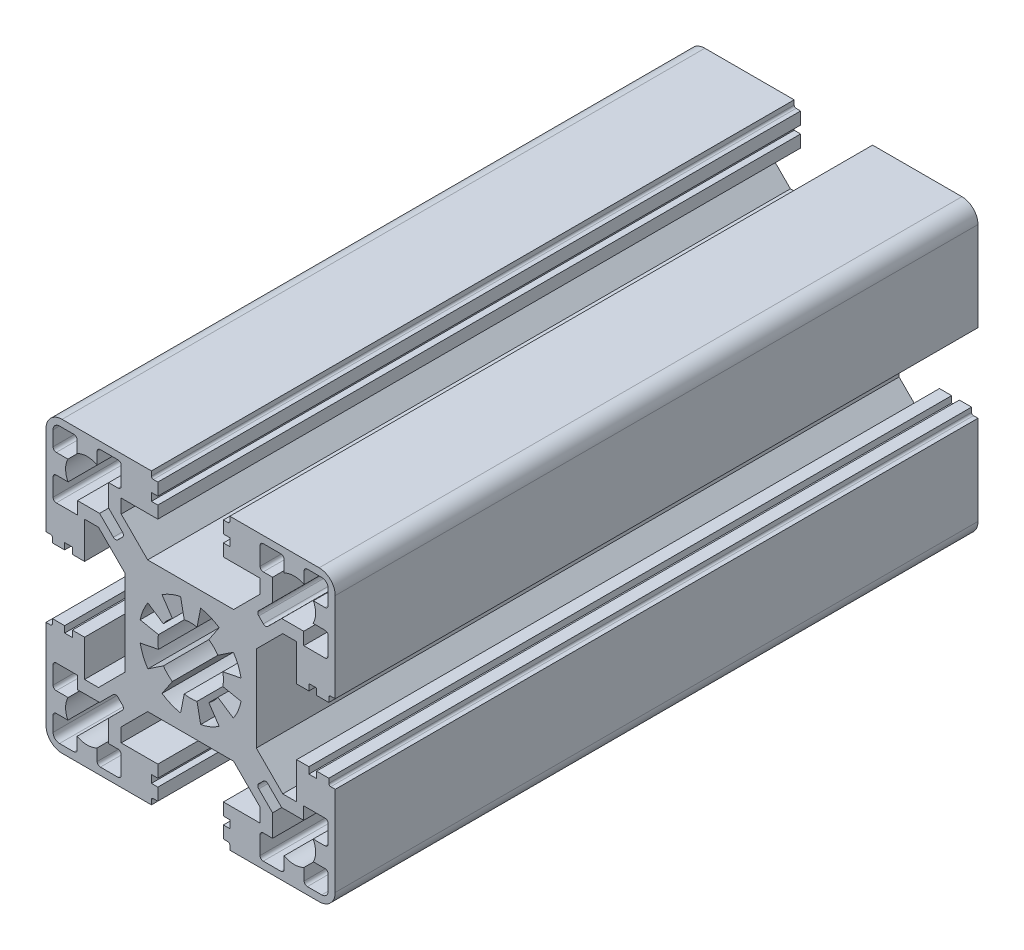
SolidWorks part; units mm, degrees
ref_plane "前视基准面" through (0, 0, 0) normal (0, 0, 1) x (1, 0, 0)
ref_plane "上视基准面" through (0, 0, 0) normal (0, 1, 0) x (1, 0, 0)
ref_plane "右视基准面" through (0, 0, 0) normal (1, 0, 0) x (0, 0, -1)
sketch "草图1" plane through (0, 0, 0) normal (0, 0, 1) x (1, 0, 0)
  line L0 (-5.3716, 23.257) -> (-19.2716, 23.257)
  line L1 (-21.7716, 20.757) -> (-21.7716, 6.857)
  line L2 (-4.3716, 17.257) -> (-10.0716, 17.257)
  line L3 (-15.7716, 11.557) -> (-15.7716, 5.857)
  line L4 (-4.3716, 22.257) -> (-5.0716, 22.257)
  line L5 (-5.3716, 22.557) -> (-5.3716, 23.257)
  line L6 (-21.7716, 6.857) -> (-21.0716, 6.857)
  line L7 (-20.7716, 6.557) -> (-20.7716, 5.857)
  line L8 (-15.7716, 11.557) -> (-13.6071, 11.557)
  line L9 (-18.8716, 6.857) -> (-17.6716, 6.857)
  line L10 (-20.7716, 5.857) -> (-18.8716, 5.857)
  line L11 (-17.6716, 5.857) -> (-15.7716, 5.857)
  line L12 (-10.0716, 17.257) -> (-10.0716, 15.0925)
  line L13 (-5.3716, 20.357) -> (-5.3716, 19.157)
  line L14 (-4.3716, 22.257) -> (-4.3716, 20.357)
  line L15 (-4.3716, 19.157) -> (-4.3716, 17.257)
  line L16 (-4.3716, 19.157) -> (-5.3716, 19.157)
  line L17 (-4.3716, 20.357) -> (-5.3716, 20.357)
  line L19 (-17.6716, 5.857) -> (-17.6716, 6.857)
  line L20 (-18.8716, 5.857) -> (-18.8716, 6.857)
  line L21 (6.8284, 23.257) -> (20.7284, 23.257)
  line L22 (23.2284, 20.757) -> (23.2284, 6.857)
  line L23 (5.8284, 17.257) -> (11.5284, 17.257)
  line L24 (17.2284, 11.557) -> (17.2284, 5.857)
  line L25 (5.8284, 22.257) -> (6.5284, 22.257)
  line L26 (6.8284, 22.557) -> (6.8284, 23.257)
  line L27 (23.2284, 6.857) -> (22.5284, 6.857)
  line L28 (22.2284, 6.557) -> (22.2284, 5.857)
  line L29 (17.2284, 11.557) -> (15.0639, 11.557)
  line L30 (20.3284, 6.857) -> (19.1284, 6.857)
  line L31 (22.2284, 5.857) -> (20.3284, 5.857)
  line L32 (19.1284, 5.857) -> (17.2284, 5.857)
  line L33 (11.5284, 17.257) -> (11.5284, 15.0925)
  line L34 (6.8284, 20.357) -> (6.8284, 19.157)
  line L35 (5.8284, 19.157) -> (6.8284, 19.157)
  line L36 (5.8284, 20.357) -> (6.8284, 20.357)
  line L38 (19.1284, 5.857) -> (19.1284, 6.857)
  line L39 (20.3284, 5.857) -> (20.3284, 6.857)
  line L40 (5.8284, 22.257) -> (5.8284, 20.357)
  line L41 (5.8284, 19.157) -> (5.8284, 17.257)
  line L42 (-5.3716, -21.743) -> (-19.2716, -21.743)
  line L43 (-21.7716, -19.243) -> (-21.7716, -5.343)
  line L44 (-4.3716, -15.743) -> (-10.0716, -15.743)
  line L45 (-15.7716, -10.043) -> (-15.7716, -4.343)
  line L46 (-4.3716, -20.743) -> (-5.0716, -20.743)
  line L47 (-5.3716, -21.043) -> (-5.3716, -21.743)
  line L48 (-21.7716, -5.343) -> (-21.0716, -5.343)
  line L49 (-20.7716, -5.043) -> (-20.7716, -4.343)
  line L50 (-15.7716, -10.043) -> (-13.6071, -10.043)
  line L51 (-18.8716, -5.343) -> (-17.6716, -5.343)
  line L52 (-20.7716, -4.343) -> (-18.8716, -4.343)
  line L53 (-17.6716, -4.343) -> (-15.7716, -4.343)
  line L54 (-10.0716, -15.743) -> (-10.0716, -13.5785)
  line L55 (-5.3716, -18.843) -> (-5.3716, -17.643)
  line L56 (-4.3716, -20.743) -> (-4.3716, -18.843)
  line L57 (-4.3716, -17.643) -> (-4.3716, -15.743)
  line L58 (-4.3716, -17.643) -> (-5.3716, -17.643)
  line L59 (-4.3716, -18.843) -> (-5.3716, -18.843)
  line L61 (-17.6716, -4.343) -> (-17.6716, -5.343)
  line L62 (-18.8716, -4.343) -> (-18.8716, -5.343)
  line L63 (6.8284, -21.743) -> (20.7284, -21.743)
  line L64 (23.2284, -19.243) -> (23.2284, -5.343)
  line L65 (5.8284, -15.743) -> (11.5284, -15.743)
  line L66 (17.2284, -10.043) -> (17.2284, -4.343)
  line L67 (5.8284, -20.743) -> (6.5284, -20.743)
  line L68 (6.8284, -21.043) -> (6.8284, -21.743)
  line L69 (23.2284, -5.343) -> (22.5284, -5.343)
  line L70 (22.2284, -5.043) -> (22.2284, -4.343)
  line L71 (17.2284, -10.043) -> (15.0639, -10.043)
  line L72 (20.3284, -5.343) -> (19.1284, -5.343)
  line L73 (22.2284, -4.343) -> (20.3284, -4.343)
  line L74 (19.1284, -4.343) -> (17.2284, -4.343)
  line L75 (11.5284, -15.743) -> (11.5284, -13.5785)
  line L76 (6.8284, -18.843) -> (6.8284, -17.643)
  line L77 (5.8284, -17.643) -> (6.8284, -17.643)
  line L78 (5.8284, -18.843) -> (6.8284, -18.843)
  line L80 (19.1284, -4.343) -> (19.1284, -5.343)
  line L81 (20.3284, -4.343) -> (20.3284, -5.343)
  line L82 (5.8284, -20.743) -> (5.8284, -18.843)
  line L83 (5.8284, -17.643) -> (5.8284, -15.743)
  line L84 (-9.4916, 7.4415) -> (-9.4916, -5.9275)
  line L85 (-5.9561, -9.463) -> (7.4129, -9.463)
  line L86 (10.9484, -5.9275) -> (10.9484, 7.4415)
  line L87 (7.4129, 10.977) -> (-5.9561, 10.977)
  line L88 (-3.7161, -5.8947) -> (-2.105, -3.4835)
  line L89 (-0.8323, -7.0893) -> (-0.2665, -4.245)
  line L90 (2.2891, -7.0893) -> (1.7234, -4.245)
  line L91 (5.173, -5.8947) -> (3.5618, -3.4835)
  line L92 (7.3802, -3.6875) -> (4.9689, -2.0764)
  line L93 (8.5747, -0.8037) -> (5.7304, -0.2379)
  line L94 (8.5747, 2.3177) -> (5.7304, 1.752)
  line L95 (7.3802, 5.2016) -> (4.9689, 3.5904)
  line L96 (5.173, 7.4088) -> (3.5618, 4.9975)
  line L97 (2.2891, 8.6033) -> (1.7234, 5.759)
  line L98 (-0.8323, 8.6033) -> (-0.2665, 5.759)
  line L99 (-3.7161, 7.4088) -> (-2.105, 4.9975)
  line L100 (-5.9233, 5.2016) -> (-3.5121, 3.5904)
  line L101 (-7.1179, 2.3177) -> (-4.2736, 1.752)
  line L102 (-7.1179, -0.8037) -> (-4.2736, -0.2379)
  line L103 (-5.9233, -3.6875) -> (-3.5121, -2.0764)
  line L104 (-10.0716, 15.0925) -> (-5.9561, 10.977)
  line L105 (-13.6071, 11.557) -> (-9.4916, 7.4415)
  line L106 (11.5284, 15.0925) -> (7.4129, 10.977)
  line L107 (15.0639, 11.557) -> (10.9484, 7.4415)
  line L108 (-10.0716, -13.5785) -> (-5.9561, -9.463)
  line L109 (-13.6071, -10.043) -> (-9.4916, -5.9275)
  line L110 (11.5284, -13.5785) -> (7.4129, -9.463)
  line L111 (15.0639, -10.043) -> (10.9484, -5.9275)
  line L113 (-20.6716, 21.157) -> (-20.6716, 18.857)
  line L114 (-20.1716, 18.357) -> (-18.367, 18.357)
  line L115 (-12.0216, 18.357) -> (-10.5716, 18.357)
  line L116 (-10.0716, 18.857) -> (-10.0716, 21.657)
  line L117 (-10.5716, 22.157) -> (-13.3116, 22.157)
  line L118 (-13.8116, 21.657) -> (-13.8116, 19.8216)
  line L120 (-16.9316, 19.8216) -> (-16.9316, 21.657)
  line L121 (-17.4316, 22.157) -> (-19.6716, 22.157)
  line L122 (-12.0216, 14.9212) -> (-12.0216, 18.357)
  line L123 (-13.4358, 13.507) -> (-11.2924, 11.3636)
  line L124 (-12.0216, 14.9212) -> (-9.8782, 12.7778)
  line L125 (-10.5853, 11.3636) -> (-9.8782, 12.0707)
  line L126 (-13.4358, 13.507) -> (-16.8716, 13.507)
  line L127 (-18.3362, 15.297) -> (-20.1716, 15.297)
  line L129 (-20.6716, 14.797) -> (-20.6716, 12.057)
  line L130 (-20.1716, 11.557) -> (-16.8716, 11.557)
  line L131 (-16.8716, 13.507) -> (-16.8716, 11.557)
  line L149 (13.4784, 18.357) -> (12.0284, 18.357)
  line L150 (11.5284, 18.857) -> (11.5284, 21.657)
  line L151 (12.0284, 22.157) -> (14.7684, 22.157)
  line L152 (15.2684, 21.657) -> (15.2684, 19.8216)
  line L153 (18.3884, 19.8216) -> (18.3884, 21.657)
  line L154 (18.8884, 22.157) -> (21.1284, 22.157)
  line L155 (22.1284, 21.157) -> (22.1284, 18.857)
  line L156 (21.6284, 18.357) -> (19.8238, 18.357)
  line L157 (19.793, 15.297) -> (21.6284, 15.297)
  line L158 (22.1284, 14.797) -> (22.1284, 12.057)
  line L159 (21.6284, 11.557) -> (18.3284, 11.557)
  line L160 (18.3284, 11.557) -> (18.3284, 13.507)
  line L161 (18.3284, 13.507) -> (14.8926, 13.507)
  line L162 (14.8926, 13.507) -> (12.7492, 11.3636)
  line L163 (12.0421, 11.3636) -> (11.335, 12.0707)
  line L164 (11.335, 12.7778) -> (13.4784, 14.9212)
  line L165 (13.4784, 14.9212) -> (13.4784, 18.357)
  line L166 (-12.0216, -16.818) -> (-10.5716, -16.818)
  line L167 (-10.0716, -17.318) -> (-10.0716, -20.118)
  line L168 (-10.5716, -20.618) -> (-13.3116, -20.618)
  line L169 (-13.8116, -20.118) -> (-13.8116, -18.2826)
  line L170 (-16.9316, -18.2826) -> (-16.9316, -20.118)
  line L171 (-17.4316, -20.618) -> (-19.6716, -20.618)
  line L172 (-20.6716, -19.618) -> (-20.6716, -17.318)
  line L173 (-20.1716, -16.818) -> (-18.367, -16.818)
  line L174 (-18.3362, -13.758) -> (-20.1716, -13.758)
  line L175 (-20.6716, -13.258) -> (-20.6716, -10.518)
  line L176 (-20.1716, -10.018) -> (-16.8716, -10.018)
  line L177 (-16.8716, -10.018) -> (-16.8716, -11.968)
  line L178 (-16.8716, -11.968) -> (-13.4358, -11.968)
  line L179 (-13.4358, -11.968) -> (-11.2924, -9.8246)
  line L180 (-10.5853, -9.8246) -> (-9.8782, -10.5317)
  line L181 (-9.8782, -11.2388) -> (-12.0216, -13.3822)
  line L182 (-12.0216, -13.3822) -> (-12.0216, -16.818)
  line L183 (13.4784, -16.818) -> (12.0284, -16.818)
  line L184 (11.5284, -17.318) -> (11.5284, -20.118)
  line L185 (12.0284, -20.618) -> (14.7684, -20.618)
  line L186 (15.2684, -20.118) -> (15.2684, -18.2826)
  line L187 (18.3884, -18.2826) -> (18.3884, -20.118)
  line L188 (18.8884, -20.618) -> (21.1284, -20.618)
  line L189 (22.1284, -19.618) -> (22.1284, -17.318)
  line L190 (21.6284, -16.818) -> (19.8238, -16.818)
  line L191 (19.793, -13.758) -> (21.6284, -13.758)
  line L192 (22.1284, -13.258) -> (22.1284, -10.518)
  line L193 (21.6284, -10.018) -> (18.3284, -10.018)
  line L194 (18.3284, -10.018) -> (18.3284, -11.968)
  line L195 (18.3284, -11.968) -> (14.8926, -11.968)
  line L196 (14.8926, -11.968) -> (12.7492, -9.8246)
  line L197 (12.0421, -9.8246) -> (11.335, -10.5317)
  line L198 (11.335, -11.2388) -> (13.4784, -13.3822)
  line L199 (13.4784, -13.3822) -> (13.4784, -16.818)
  arc A0 (-19.2716, 23.257) -> (-21.7716, 20.757) centre (-19.2716, 20.757) ccw
  arc A1 (-5.3716, 22.557) -> (-5.0716, 22.257) centre (-5.0716, 22.557) ccw
  arc A2 (-20.7716, 6.557) -> (-21.0716, 6.857) centre (-21.0716, 6.557) ccw
  arc A3 (23.2284, 20.757) -> (20.7284, 23.257) centre (20.7284, 20.757) ccw
  arc A4 (6.5284, 22.257) -> (6.8284, 22.557) centre (6.5284, 22.557) ccw
  arc A5 (22.5284, 6.857) -> (22.2284, 6.557) centre (22.5284, 6.557) ccw
  arc A6 (-21.7716, -19.243) -> (-19.2716, -21.743) centre (-19.2716, -19.243) ccw
  arc A7 (-5.0716, -20.743) -> (-5.3716, -21.043) centre (-5.0716, -21.043) ccw
  arc A8 (-21.0716, -5.343) -> (-20.7716, -5.043) centre (-21.0716, -5.043) ccw
  arc A9 (20.7284, -21.743) -> (23.2284, -19.243) centre (20.7284, -19.243) ccw
  arc A10 (6.8284, -21.043) -> (6.5284, -20.743) centre (6.5284, -21.043) ccw
  arc A11 (22.2284, -5.043) -> (22.5284, -5.343) centre (22.5284, -5.043) ccw
  arc A12 (-0.2665, -4.245) -> (1.7234, -4.245) centre (0.7284, 0.757) ccw
  arc A13 (3.5618, -3.4835) -> (4.9689, -2.0764) centre (0.7284, 0.757) ccw
  arc A14 (5.7304, -0.2379) -> (5.7304, 1.752) centre (0.7284, 0.757) ccw
  arc A15 (4.9689, 3.5904) -> (3.5618, 4.9975) centre (0.7284, 0.757) ccw
  arc A16 (1.7234, 5.759) -> (-0.2665, 5.759) centre (0.7284, 0.757) ccw
  arc A17 (-2.105, 4.9975) -> (-3.5121, 3.5904) centre (0.7284, 0.757) ccw
  arc A18 (-4.2736, 1.752) -> (-4.2736, -0.2379) centre (0.7284, 0.757) ccw
  arc A19 (-3.5121, -2.0764) -> (-2.105, -3.4835) centre (0.7284, 0.757) ccw
  arc A20 (-3.7161, -5.8947) -> (-0.8323, -7.0893) centre (0.7284, 0.757) ccw
  arc A21 (2.2891, -7.0893) -> (5.173, -5.8947) centre (0.7284, 0.757) ccw
  arc A22 (7.3802, -3.6875) -> (8.5747, -0.8037) centre (0.7284, 0.757) ccw
  arc A23 (8.5747, 2.3177) -> (7.3802, 5.2016) centre (0.7284, 0.757) ccw
  arc A24 (5.173, 7.4088) -> (2.2891, 8.6033) centre (0.7284, 0.757) ccw
  arc A25 (-0.8323, 8.6033) -> (-3.7161, 7.4088) centre (0.7284, 0.757) ccw
  arc A26 (-5.9233, 5.2016) -> (-7.1179, 2.3177) centre (0.7284, 0.757) ccw
  arc A27 (-7.1179, -0.8037) -> (-5.9233, -3.6875) centre (0.7284, 0.757) ccw
  arc A28 (-18.367, 18.357) -> (-18.3362, 15.297) centre (-15.3716, 16.857) ccw
  arc A29 (-13.8116, 19.8216) -> (-16.9316, 19.8216) centre (-15.3716, 16.857) ccw
  arc A30 (-19.6716, 22.157) -> (-20.6716, 21.157) centre (-19.6716, 21.157) ccw
  arc A31 (-20.6716, 18.857) -> (-20.1716, 18.357) centre (-20.1716, 18.857) ccw
  arc A32 (-10.5716, 18.357) -> (-10.0716, 18.857) centre (-10.5716, 18.857) ccw
  arc A33 (-10.0716, 21.657) -> (-10.5716, 22.157) centre (-10.5716, 21.657) ccw
  arc A34 (-13.3116, 22.157) -> (-13.8116, 21.657) centre (-13.3116, 21.657) ccw
  arc A35 (-16.9316, 21.657) -> (-17.4316, 22.157) centre (-17.4316, 21.657) ccw
  arc A36 (-11.2924, 11.3636) -> (-10.5853, 11.3636) centre (-10.9388, 11.7172) ccw
  arc A37 (-9.8782, 12.0707) -> (-9.8782, 12.7778) centre (-10.2317, 12.4243) ccw
  arc A38 (-20.1716, 15.297) -> (-20.6716, 14.797) centre (-20.1716, 14.797) ccw
  arc A39 (-20.6716, 12.057) -> (-20.1716, 11.557) centre (-20.1716, 12.057) ccw
  arc A52 (11.5284, 18.857) -> (12.0284, 18.357) centre (12.0284, 18.857) ccw
  arc A53 (12.0284, 22.157) -> (11.5284, 21.657) centre (12.0284, 21.657) ccw
  arc A54 (15.2684, 21.657) -> (14.7684, 22.157) centre (14.7684, 21.657) ccw
  arc A55 (18.3884, 19.8216) -> (15.2684, 19.8216) centre (16.8284, 16.857) ccw
  arc A56 (18.8884, 22.157) -> (18.3884, 21.657) centre (18.8884, 21.657) ccw
  arc A57 (22.1284, 21.157) -> (21.1284, 22.157) centre (21.1284, 21.157) ccw
  arc A58 (21.6284, 18.357) -> (22.1284, 18.857) centre (21.6284, 18.857) ccw
  arc A59 (19.793, 15.297) -> (19.8238, 18.357) centre (16.8284, 16.857) ccw
  arc A60 (22.1284, 14.797) -> (21.6284, 15.297) centre (21.6284, 14.797) ccw
  arc A61 (21.6284, 11.557) -> (22.1284, 12.057) centre (21.6284, 12.057) ccw
  arc A62 (12.0421, 11.3636) -> (12.7492, 11.3636) centre (12.3957, 11.7172) ccw
  arc A63 (11.335, 12.7778) -> (11.335, 12.0707) centre (11.6886, 12.4243) ccw
  arc A64 (-10.0716, -17.318) -> (-10.5716, -16.818) centre (-10.5716, -17.318) ccw
  arc A65 (-10.5716, -20.618) -> (-10.0716, -20.118) centre (-10.5716, -20.118) ccw
  arc A66 (-13.8116, -20.118) -> (-13.3116, -20.618) centre (-13.3116, -20.118) ccw
  arc A67 (-16.9316, -18.2826) -> (-13.8116, -18.2826) centre (-15.3716, -15.318) ccw
  arc A68 (-17.4316, -20.618) -> (-16.9316, -20.118) centre (-17.4316, -20.118) ccw
  arc A69 (-20.6716, -19.618) -> (-19.6716, -20.618) centre (-19.6716, -19.618) ccw
  arc A70 (-20.1716, -16.818) -> (-20.6716, -17.318) centre (-20.1716, -17.318) ccw
  arc A71 (-18.3362, -13.758) -> (-18.367, -16.818) centre (-15.3716, -15.318) ccw
  arc A72 (-20.6716, -13.258) -> (-20.1716, -13.758) centre (-20.1716, -13.258) ccw
  arc A73 (-20.1716, -10.018) -> (-20.6716, -10.518) centre (-20.1716, -10.518) ccw
  arc A74 (-10.5853, -9.8246) -> (-11.2924, -9.8246) centre (-10.9388, -10.1781) ccw
  arc A75 (-9.8782, -11.2388) -> (-9.8782, -10.5317) centre (-10.2317, -10.8853) ccw
  arc A76 (12.0284, -16.818) -> (11.5284, -17.318) centre (12.0284, -17.318) ccw
  arc A77 (11.5284, -20.118) -> (12.0284, -20.618) centre (12.0284, -20.118) ccw
  arc A78 (14.7684, -20.618) -> (15.2684, -20.118) centre (14.7684, -20.118) ccw
  arc A79 (15.2684, -18.2826) -> (18.3884, -18.2826) centre (16.8284, -15.318) ccw
  arc A80 (18.3884, -20.118) -> (18.8884, -20.618) centre (18.8884, -20.118) ccw
  arc A81 (21.1284, -20.618) -> (22.1284, -19.618) centre (21.1284, -19.618) ccw
  arc A82 (22.1284, -17.318) -> (21.6284, -16.818) centre (21.6284, -17.318) ccw
  arc A83 (19.8238, -16.818) -> (19.793, -13.758) centre (16.8284, -15.318) ccw
  arc A84 (21.6284, -13.758) -> (22.1284, -13.258) centre (21.6284, -13.258) ccw
  arc A85 (22.1284, -10.518) -> (21.6284, -10.018) centre (21.6284, -10.518) ccw
  arc A86 (12.7492, -9.8246) -> (12.0421, -9.8246) centre (12.3957, -10.1781) ccw
  arc A87 (11.335, -10.5317) -> (11.335, -11.2388) centre (11.6886, -10.8853) ccw
extrude "凸台-拉伸1" add sketch "草图1" along normal blind 100
